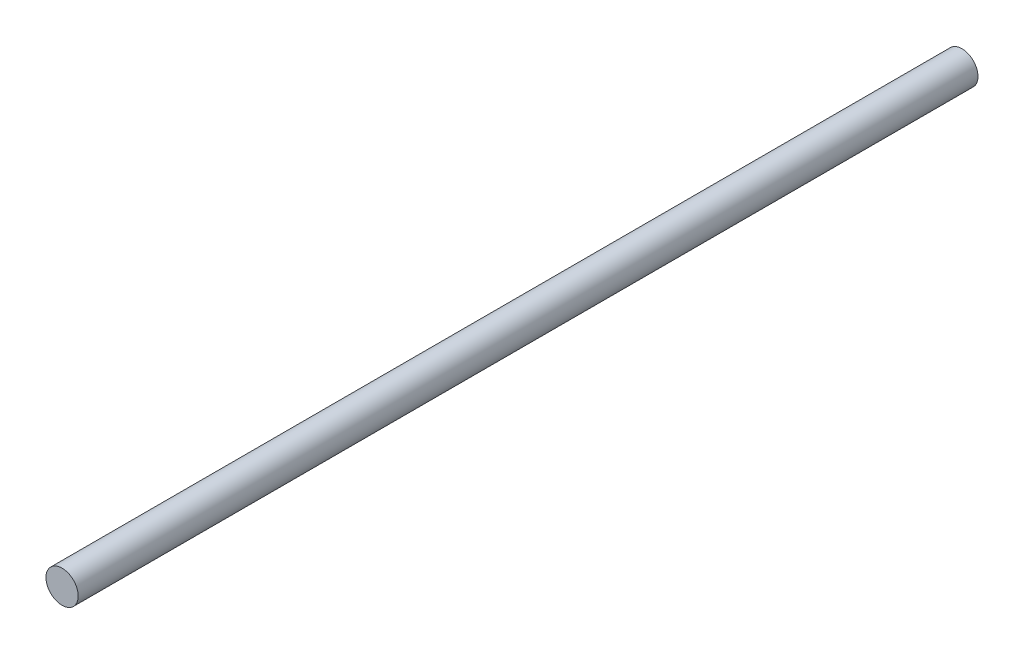
SolidWorks part; units mm, degrees
ref_plane "Front Plane" through (0, 0, 0) normal (0, 0, 1) x (1, 0, 0)
ref_plane "Top Plane" through (0, 0, 0) normal (0, 1, 0) x (1, 0, 0)
ref_plane "Right Plane" through (0, 0, 0) normal (1, 0, 0) x (0, 0, -1)
sketch "Sketch1" plane through (0, 0, 0) normal (0, 0, 1) x (1, 0, 0)
  circle A0 centre (0, 0) radius 1.5
  dimension "D1" = 3
extrude "Boss-Extrude1" add sketch "Sketch1" along normal blind 83.82
